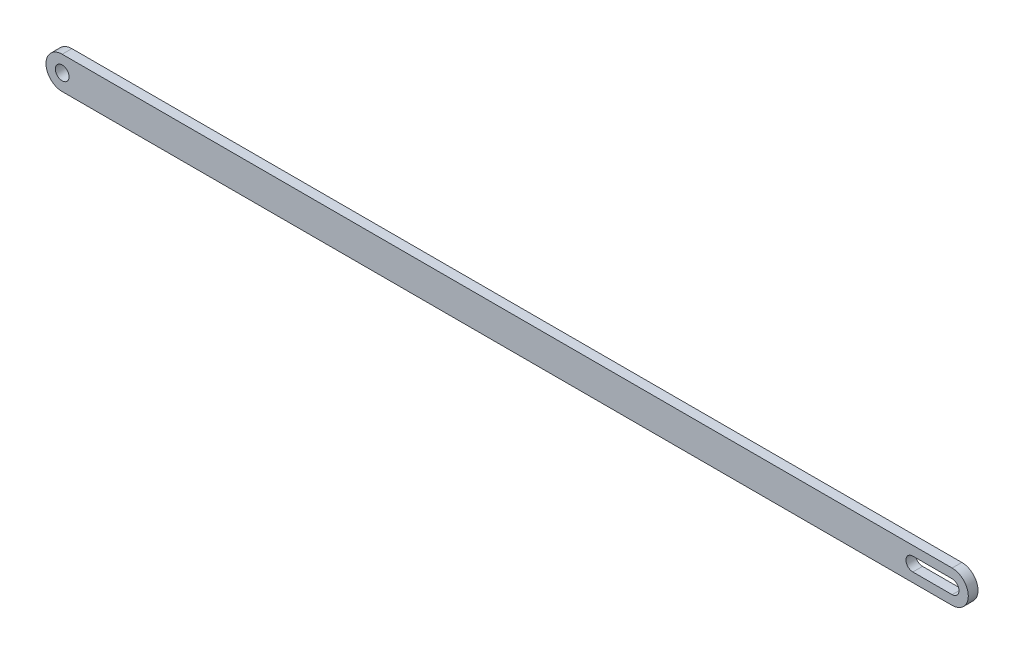
SolidWorks part; units mm, degrees
ref_plane "前视基准面" through (0, 0, 0) normal (0, 0, 1) x (1, 0, 0)
ref_plane "上视基准面" through (0, 0, 0) normal (0, 1, 0) x (1, 0, 0)
ref_plane "右视基准面" through (0, 0, 0) normal (1, 0, 0) x (0, 0, -1)
sketch "草图1" plane through (0, 0, 0) normal (0, 0, 1) x (1, 0, 0)
  line L0 (-53.8502, 4) -> (166.1498, 4)
  line L1 (-53.8502, -4) -> (166.1498, -4)
  line L2 (166.1498, 1.7) -> (156.4387, 1.7)
  line L10 (156.4387, -1.7) -> (166.1498, -1.7)
  arc A4 (-53.8502, 4) -> (-53.8502, -4) centre (-53.8502, 0) ccw
  arc A18 (166.1498, -4) -> (166.1498, 4) centre (166.1498, 0) ccw construction
  arc A19 (166.1498, -4) -> (166.1498, 4) centre (166.1498, 0) ccw
  arc A21 (-53.8502, 4) -> (-53.8502, -4) centre (-53.8502, 0) ccw
  circle A22 centre (-53.8502, 0) radius 1.7
  arc A23 (166.1498, -1.7) -> (166.1498, 1.7) centre (166.1498, 0) ccw
  arc A24 (156.4387, 1.7) -> (156.4387, -1.7) centre (156.4387, 0) ccw
  point P22 (0, 0)
  dimension "D1" = 220
  dimension "D2" = 220
extrude "凸台-拉伸1" add sketch "草图1" along normal blind 2.4 contours L1 A19 L0 A4 A24 L2 A23 L10 A22
